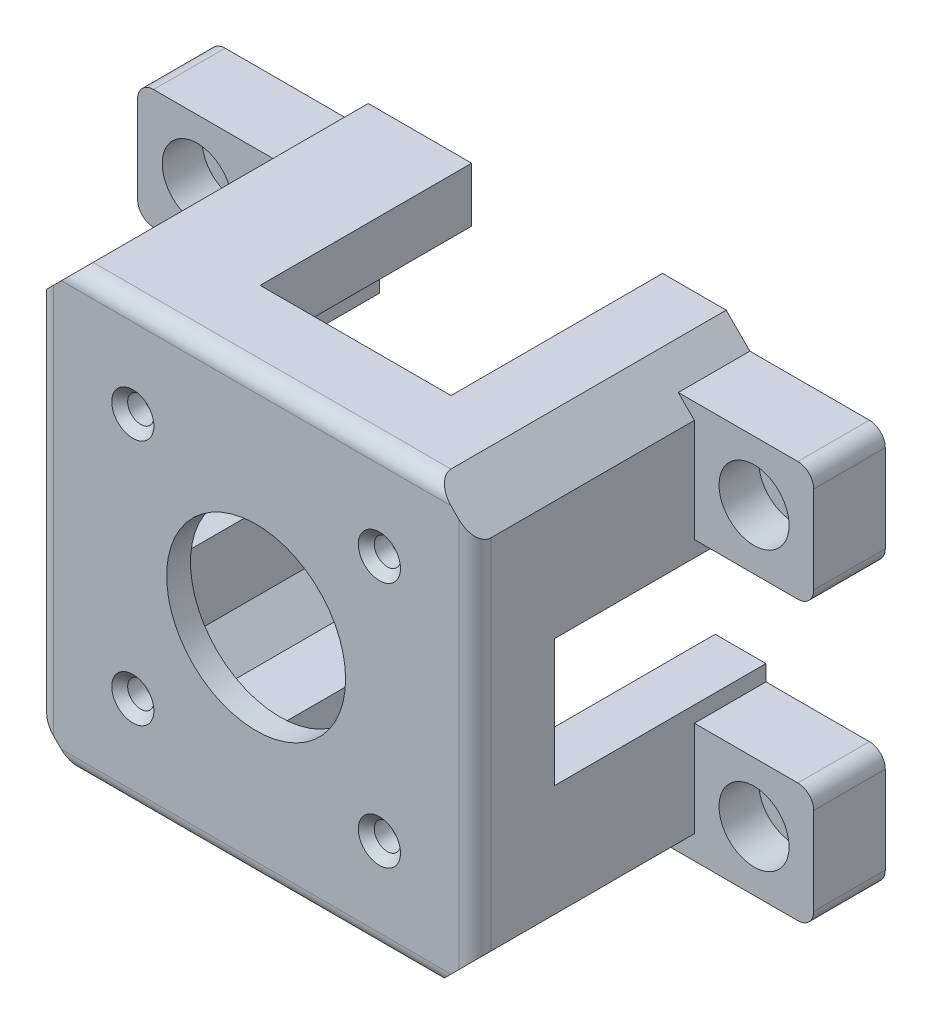
SolidWorks part; units mm, degrees
ref_plane "Front Plane" through (0, 0, 0) normal (0, 0, 1) x (1, 0, 0)
ref_plane "Top Plane" through (0, 0, 0) normal (0, 1, 0) x (1, 0, 0)
ref_plane "Right Plane" through (0, 0, 0) normal (1, 0, 0) x (0, 0, -1)
sketch "Sketch2" plane through (0, 0, 0) normal (0, 0, 1) x (1, 0, 0)
  line L1 (-27.5, -27.0238) -> (27.5, -27.0238)
  line L2 (-27.5, -27.0238) -> (-27.5, 27.9762)
  line L3 (-27.5, 27.9762) -> (27.5, 27.9762)
  line L4 (27.5, -27.0238) -> (27.5, 27.9762)
  line L5 (-27.5, -27.0238) -> (27.5, 27.9762) construction
  line L6 (-27.5, 27.9762) -> (27.5, -27.0238) construction
  line L16 (21.1184, 17.2806) -> (17.2806, 21.1184)
  line L17 (17.2806, 21.1184) -> (-17.2806, 21.1184)
  line L18 (-17.2806, 21.1184) -> (-21.1184, 17.2806)
  line L19 (-21.1184, 17.2806) -> (-21.1184, -17.2806)
  line L20 (-21.1184, -17.2806) -> (-17.2806, -21.1184)
  line L21 (-17.2806, -21.1184) -> (17.2806, -21.1184)
  line L22 (17.2806, -21.1184) -> (21.1184, -17.2806)
  line L23 (21.1184, -17.2806) -> (21.1184, 17.2806)
  circle A2 centre (0, 0.4762) radius 16.593
  dimension "D1" = 55
  dimension "D2" = 55
extrude "Boss-Extrude1" add sketch "Sketch2" along normal blind 33.6 contours L1 L4 L3 L2 L23 L22 L21 L20 L19 L18 L17 L16
sketch "Sketch3" plane through (0, 0, 33.6) normal (0, 0, 1) x (1, 0, 0)
  line L0 (-27.5, 27.9762) -> (27.5, -27.0238)
  line L1 (-27.5, -27.0238) -> (27.5, -27.0238)
  line L2 (-27.5, -27.0238) -> (-27.5, 27.9762)
  line L3 (-27.5, 27.9762) -> (27.5, 27.9762)
  line L4 (27.5, -27.0238) -> (27.5, 27.9762)
  line L5 (27.5, 27.9762) -> (-27.5, -27.0238)
  circle A0 centre (0, 0.4762) radius 11.25
  line M1 (21.1184, 17.2806) -> (21.1184, -17.2806)
  line M2 (21.1184, -17.2806) -> (17.2806, -21.1184)
  line M3 (17.2806, -21.1184) -> (-17.2806, -21.1184)
  line M4 (-17.2806, -21.1184) -> (-21.1184, -17.2806)
  line M5 (-21.1184, -17.2806) -> (-21.1184, 17.2806)
  line M6 (-21.1184, 17.2806) -> (-17.2806, 21.1184)
  line M7 (-17.2806, 21.1184) -> (17.2806, 21.1184)
  line M8 (17.2806, 21.1184) -> (21.1184, 17.2806)
  line M9 (-27.5, -27.0238) -> (27.5, -27.0238)
  line M10 (27.5, -27.0238) -> (27.5, 27.9762)
  line M11 (27.5, 27.9762) -> (-27.5, 27.9762)
  line M12 (-27.5, 27.9762) -> (-27.5, -27.0238)
  dimension "D1" = 22.5
extrude "Boss-Extrude2" add sketch "Sketch3" along normal blind 3 contours A0 L0 L5 M6 M5 M4 | A0 L5 L0 M4 M3 M2 | A0 L0 L5 M2 M1 M8 | A0 L5 L0 M8 M7 M6 | L5 L0 M4 M5 M6 M12 | L5 L0 M4 M9 M2 M3 | L5 L0 M10 M8 M1 M2 | L5 L0 M11 M6 M7 M8
sketch "Sketch4" plane through (0, 0, 0) normal (0, 0, -1) x (-1, 0, 0)
  line L0 (0, 0) -> (-27.5, 0)
  line L1 (-27.5, -27.0238) -> (-27.5, 27.9762) construction
  line L2 (-27.5, 0) -> (-27.5, 10)
  line L3 (0, 0) -> (0, 34.2278) construction
  line L4 (-27.5, 10) -> (-42.5, 10)
  line L5 (-27.5, 10) -> (-27.5, 25)
  line L6 (-27.5, 25) -> (-42.5, 25)
  line L7 (-42.5, 10) -> (-42.5, 25)
  line L8 (42.5, 10) -> (42.5, 25)
  line L9 (27.5, 25) -> (42.5, 25)
  line L10 (27.5, 10) -> (27.5, 25)
  line L11 (27.5, 10) -> (42.5, 10)
  line L16 (-42.5, -10) -> (-42.5, -25)
  line L17 (-27.5, -25) -> (-42.5, -25)
  line L18 (-27.5, -10) -> (-27.5, -25)
  line L19 (-27.5, -10) -> (-42.5, -10)
  line L20 (27.5, -27.0238) -> (-27.5, -27.0238) construction
  line L21 (25, -27.0238) -> (10, -27.0238)
  line L22 (25, -27.0238) -> (25, -42.0238)
  line L23 (25, -42.0238) -> (10, -42.0238)
  line L24 (10, -27.0238) -> (10, -42.0238)
  circle A1 centre (-35, 17.5) radius 2.6
  circle A2 centre (35, 17.5) radius 2.6
  circle A4 centre (-35, -17.5) radius 2.6
  circle A5 centre (17.5, -34.5238) radius 2.6
  dimension "D1" = 10
  dimension "D4" = 5.2
  dimension "D5" = 7.5
  dimension "D10" = 5.2
  dimension "D2" = 15
  dimension "D3" = 15
  dimension "D6" = 7.5
  dimension "D7" = 15
  dimension "D8" = 15
  dimension "D9" = 10
  dimension "D11" = 7.5
  dimension "D12" = 7.5
extrude "Boss-Extrude3" add sketch "Sketch4" against normal blind 9 contours L7 L4 L11 L6 A1 | L11 L19 L16 L17 A4 | A5 | A2 | L22 L23 L24 L21
sketch "Sketch6" plane through (0, 0, 9) normal (0, 0, 1) x (1, 0, 0)
  line L2 (20.955, 0) -> (-20.955, 0) construction
  line L7 (-10, -27.0238) -> (-25, -27.0238)
  line L8 (-25, -27.0238) -> (-25, -42.0238)
  line L9 (-25, -42.0238) -> (-10, -42.0238)
  line L10 (-10, -42.0238) -> (-10, -27.0238)
  line L11 (-10, -27.0238) -> (-25, -27.0238)
  line L12 (-25, -27.0238) -> (-25, -42.0238)
  line L13 (-25, -42.0238) -> (-10, -42.0238)
  line L14 (-10, -42.0238) -> (-10, -27.0238)
  circle A0 centre (35, -17.5) radius 4.4
  circle A2 centre (35, 17.5) radius 4.4
  circle A3 centre (-35, 17.5) radius 4.4
  circle A4 centre (-17.5, -34.5238) radius 4.4
  circle M5 centre (35, -17.5) radius 2.6
  dimension "D1" = 8.8
  dimension "D3" = 8.8
  dimension "D2" = 0
extrude "Cut-Extrude1" cut sketch "Sketch6" against normal blind 5 contours A4 | A3 | A0 M5 | A2
chamfer "Chamfer1" distance 5 angle 45 4 edges at (27.5, -27.0238, 18.3) (-27.5, -27.0238, 18.3) (27.5, 27.9762, 18.3) (-27.5, 27.9762, 18.3)
fillet "Fillet4" radius 2 12 edges at (42.5, -10, 4.5) (42.5, -25, 4.5) (42.5, 10, 4.5) (42.5, 25, 4.5) (-42.5, 10, 4.5) (-42.5, 25, 4.5) (0, -27.0238, 36.6) (-27.5, 0.4762, 36.6) (27.5, 0.4762, 36.6) (0, 27.9762, 36.6) (-25, -42.0238, 4.5) (-10, -42.0238, 4.5)
sketch "Sketch7" plane through (0, -27.0238, 0) normal (0, -1, 0) x (1, 0, 0)
  line L0 (-10, 0) -> (22.5, 0) construction
  line L1 (-9.5, 0) -> (14.5, 0)
  line L2 (-9.5, 0) -> (-9.5, 26.6)
  line L3 (-9.5, 26.6) -> (14.5, 26.6)
  line L4 (14.5, 0) -> (14.5, 26.6)
  line L5 (22.5, 0) -> (22.5, 34.6) construction
  line L6 (-22.5, 34.6) -> (-22.5, 9) construction
  line L7 (22.5, 34.6) -> (-22.5, 34.6) construction
  dimension "D1" = 8
  dimension "D2" = 13
  dimension "D3" = 8
extrude "Cut-Extrude2" cut sketch "Sketch7" against normal blind 67
sketch "Sketch8" plane through (-27.5, 0, 0) normal (-1, 0, 0) x (0, 0, 1)
  line L0 (34.6, -22.0238) -> (34.6, 22.9762) construction
  line L1 (0, 8) -> (26.6, 8)
  line L2 (0, 8) -> (0, -8)
  line L3 (0, -8) -> (26.6, -8)
  line L4 (26.6, 8) -> (26.6, -8)
  dimension "D1" = 8
  dimension "D2" = 16
  dimension "D3" = 26.6
  dimension "D4" = 8
extrude "Cut-Extrude3" cut sketch "Sketch8" against normal blind 67
sketch "Sketch9" plane through (0, 0, 0) normal (0, 0, -1) x (-1, 0, 0)
  line L0 (-21.1184, -17.2806) -> (-21.1184, -8) construction
  line L1 (-21.1184, -8) -> (-27.5, -8) construction
  line L2 (-27.5, -8) -> (-27.5, -10) construction
  line L3 (-27.5, -10) -> (-40.5, -10) construction
  line L4 (-42.5, -12) -> (-42.5, -23) construction
  line L5 (-40.5, -25) -> (-24.5238, -25) construction
  line L6 (-24.5238, -25) -> (-22.5, -27.0238) construction
  line L7 (-22.5, -27.0238) -> (-14.5, -27.0238) construction
  line L8 (-14.5, -27.0238) -> (-14.5, -21.1184) construction
  line L9 (-14.5, -21.1184) -> (-17.2806, -21.1184) construction
  line L10 (-17.2806, -21.1184) -> (-21.1184, -17.2806) construction
  line L11 (27.5, -22.0238) -> (27.5, -8) construction
  line L12 (27.5, -8) -> (21.1184, -8) construction
  line L13 (21.1184, -8) -> (21.1184, -17.2806) construction
  line L14 (21.1184, -17.2806) -> (17.2806, -21.1184) construction
  line L15 (17.2806, -21.1184) -> (9.5, -21.1184) construction
  line L16 (9.5, -21.1184) -> (9.5, -27.0238) construction
  line L17 (9.5, -27.0238) -> (10, -27.0238) construction
  line L18 (10, -27.0238) -> (10, -40.0238) construction
  line L19 (12, -42.0238) -> (23, -42.0238) construction
  line L20 (25, -40.0238) -> (25, -24.5238) construction
  line L21 (25, -24.5238) -> (27.5, -22.0238) construction
  line L22 (21.1184, 17.2806) -> (21.1184, 8) construction
  line L23 (21.1184, 8) -> (27.5, 8) construction
  line L24 (27.5, 8) -> (27.5, 10) construction
  line L25 (27.5, 10) -> (40.5, 10) construction
  line L26 (42.5, 12) -> (42.5, 23) construction
  line L27 (40.5, 25) -> (25.4762, 25) construction
  line L28 (25.4762, 25) -> (22.5, 27.9762) construction
  line L29 (22.5, 27.9762) -> (9.5, 27.9762) construction
  line L30 (9.5, 27.9762) -> (9.5, 21.1184) construction
  line L31 (9.5, 21.1184) -> (17.2806, 21.1184) construction
  line L32 (17.2806, 21.1184) -> (21.1184, 17.2806) construction
  line L33 (-27.5, 10) -> (-27.5, 8) construction
  line L34 (-27.5, 8) -> (-21.1184, 8) construction
  line L35 (-21.1184, 8) -> (-21.1184, 17.2806) construction
  line L36 (-21.1184, 17.2806) -> (-17.2806, 21.1184) construction
  line L37 (-17.2806, 21.1184) -> (-14.5, 21.1184) construction
  line L38 (-14.5, 21.1184) -> (-14.5, 27.9762) construction
  line L39 (-14.5, 27.9762) -> (-22.5, 27.9762) construction
  line L40 (-22.5, 27.9762) -> (-25.4762, 25) construction
  line L41 (-25.4762, 25) -> (-40.5, 25) construction
  line L42 (-42.5, 23) -> (-42.5, 12) construction
  line L43 (-40.5, 10) -> (-27.5, 10) construction
  line L44 (-21.1184, -17.2806) -> (-21.1184, -8)
  line L45 (-21.1184, -8) -> (-27.5, -8)
  line L46 (-27.5, -8) -> (-27.5, -10)
  line L47 (-27.5, -10) -> (-40.5, -10)
  line L48 (-42.5, -12) -> (-42.5, -23)
  line L49 (-40.5, -25) -> (-24.5238, -25)
  line L50 (-24.5238, -25) -> (-22.5, -27.0238)
  line L51 (-22.5, -27.0238) -> (-14.5, -27.0238)
  line L52 (-14.5, -27.0238) -> (-14.5, -21.1184)
  line L53 (-14.5, -21.1184) -> (-17.2806, -21.1184)
  line L54 (-17.2806, -21.1184) -> (-21.1184, -17.2806)
  line L55 (27.5, -22.0238) -> (27.5, -8)
  line L56 (27.5, -8) -> (21.1184, -8)
  line L57 (21.1184, -8) -> (21.1184, -17.2806)
  line L58 (21.1184, -17.2806) -> (17.2806, -21.1184)
  line L59 (17.2806, -21.1184) -> (9.5, -21.1184)
  line L60 (9.5, -21.1184) -> (9.5, -27.0238)
  line L61 (9.5, -27.0238) -> (10, -27.0238)
  line L62 (10, -27.0238) -> (10, -40.0238)
  line L63 (12, -42.0238) -> (23, -42.0238)
  line L64 (25, -40.0238) -> (25, -24.5238)
  line L65 (25, -24.5238) -> (27.5, -22.0238)
  line L66 (21.1184, 17.2806) -> (21.1184, 8)
  line L67 (21.1184, 8) -> (27.5, 8)
  line L68 (27.5, 8) -> (27.5, 10)
  line L69 (27.5, 10) -> (40.5, 10)
  line L70 (42.5, 12) -> (42.5, 23)
  line L71 (40.5, 25) -> (25.4762, 25)
  line L72 (25.4762, 25) -> (22.5, 27.9762)
  line L73 (22.5, 27.9762) -> (9.5, 27.9762)
  line L74 (9.5, 27.9762) -> (9.5, 21.1184)
  line L75 (9.5, 21.1184) -> (17.2806, 21.1184)
  line L76 (17.2806, 21.1184) -> (21.1184, 17.2806)
  line L77 (-27.5, 10) -> (-27.5, 8)
  line L78 (-27.5, 8) -> (-21.1184, 8)
  line L79 (-21.1184, 8) -> (-21.1184, 17.2806)
  line L80 (-21.1184, 17.2806) -> (-17.2806, 21.1184)
  line L81 (-17.2806, 21.1184) -> (-14.5, 21.1184)
  line L82 (-14.5, 21.1184) -> (-14.5, 27.9762)
  line L83 (-14.5, 27.9762) -> (-22.5, 27.9762)
  line L84 (-22.5, 27.9762) -> (-25.4762, 25)
  line L85 (-25.4762, 25) -> (-40.5, 25)
  line L86 (-42.5, 23) -> (-42.5, 12)
  line L87 (-40.5, 10) -> (-27.5, 10)
  arc A0 (-40.5, -10) -> (-42.5, -12) centre (-40.5, -12) ccw construction
  arc A1 (-42.5, -23) -> (-40.5, -25) centre (-40.5, -23) ccw construction
  arc A2 (10, -40.0238) -> (12, -42.0238) centre (12, -40.0238) ccw construction
  arc A3 (23, -42.0238) -> (25, -40.0238) centre (23, -40.0238) ccw construction
  arc A4 (40.5, 10) -> (42.5, 12) centre (40.5, 12) ccw construction
  arc A5 (42.5, 23) -> (40.5, 25) centre (40.5, 23) ccw construction
  arc A6 (-40.5, 25) -> (-42.5, 23) centre (-40.5, 23) ccw construction
  arc A7 (-42.5, 12) -> (-40.5, 10) centre (-40.5, 12) ccw construction
  arc A8 (-40.5, -10) -> (-42.5, -12) centre (-40.5, -12) ccw
  arc A9 (-42.5, -23) -> (-40.5, -25) centre (-40.5, -23) ccw
  arc A10 (10, -40.0238) -> (12, -42.0238) centre (12, -40.0238) ccw
  arc A11 (23, -42.0238) -> (25, -40.0238) centre (23, -40.0238) ccw
  arc A12 (40.5, 10) -> (42.5, 12) centre (40.5, 12) ccw
  arc A13 (42.5, 23) -> (40.5, 25) centre (40.5, 23) ccw
  arc A14 (-40.5, 25) -> (-42.5, 23) centre (-40.5, 23) ccw
  arc A15 (-42.5, 12) -> (-40.5, 10) centre (-40.5, 12) ccw
mirror "Mirror2" about plane through (-25, -42.0238, 9) normal (0, 1, 0) of bodies 107
delete or keep bodies "Body-Delete/Keep 1" type delete bodies bodies 107
mirror "Mirror3"
delete or keep bodies "Body-Delete/Keep 2" type delete bodies bodies 110
sketch "Sketch10" plane through (0, 0, 36.6) normal (0, 0, 1) x (1, 0, 0)
  line L1 (-15.5, -155.0238) -> (15.5, -155.0238) construction
  line L2 (-15.5, -155.0238) -> (-15.5, -124.0238) construction
  line L3 (-15.5, -124.0238) -> (15.5, -124.0238) construction
  line L4 (15.5, -155.0238) -> (15.5, -124.0238) construction
  line L5 (-15.5, -155.0238) -> (15.5, -124.0238) construction
  line L6 (-15.5, -124.0238) -> (15.5, -155.0238) construction
  line L8 (-25.5, -164.0238) -> (-24.5, -165.0238)
  line L9 (-24.5, -165.0238) -> (24.5, -165.0238)
  line L10 (24.5, -165.0238) -> (25.5, -164.0238)
  line L11 (25.5, -164.0238) -> (25.5, -115.0238)
  line L12 (25.5, -115.0238) -> (24.5, -114.0238)
  line L13 (24.5, -114.0238) -> (-24.5, -114.0238)
  line L14 (-24.5, -114.0238) -> (-25.5, -115.0238)
  line L15 (-25.5, -115.0238) -> (-25.5, -164.0238)
  line L16 (-25.5, -164.0238) -> (-24.5, -165.0238)
  line L17 (-24.5, -165.0238) -> (24.5, -165.0238)
  line L18 (24.5, -165.0238) -> (25.5, -164.0238)
  line L19 (25.5, -164.0238) -> (25.5, -115.0238)
  line L20 (25.5, -115.0238) -> (24.5, -114.0238)
  line L21 (24.5, -114.0238) -> (-24.5, -114.0238)
  line L22 (-24.5, -114.0238) -> (-25.5, -115.0238)
  line L23 (-25.5, -115.0238) -> (-25.5, -164.0238)
  circle A0 centre (15.5, -155.0238) radius 1.65
  circle A1 centre (-15.5, -155.0238) radius 1.65
  circle A2 centre (-15.5, -124.0238) radius 1.65
  circle A3 centre (15.5, -124.0238) radius 1.65
  point P2 (0, -139.5238)
  dimension "D3" = 3.3
  dimension "D2" = 31
  dimension "D1" = 0
extrude "Cut-Extrude4" cut sketch "Sketch10" against normal blind 10 contours A2 | A3 | A0 | A1
chamfer "Chamfer2" distance 1 angle 45 4 edges at (-13.85, -155.0238, 36.6) (17.15, -155.0238, 36.6) (17.15, -124.0238, 36.6) (-13.85, -124.0238, 36.6)
